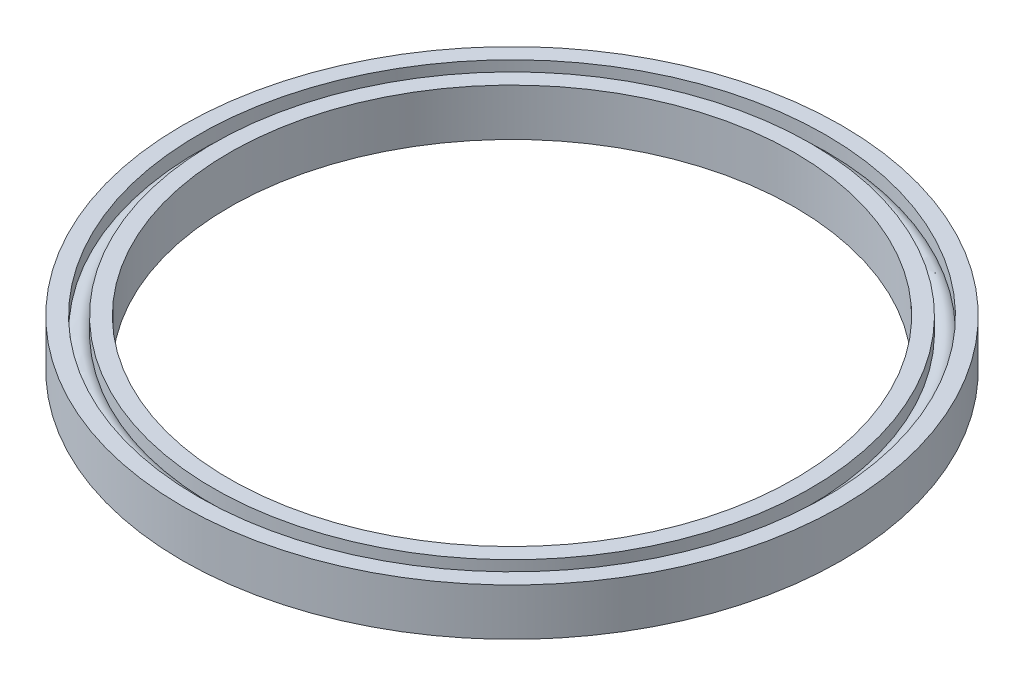
SolidWorks part; units mm, degrees
material "镀铬不锈钢"
ref_plane "前视基准面" through (0, 0, 0) normal (0, 0, 1) x (1, 0, 0)
ref_plane "上视基准面" through (0, 0, 0) normal (0, 1, 0) x (1, 0, 0)
ref_plane "右视基准面" through (0, 0, 0) normal (1, 0, 0) x (0, 0, -1)
other "Configuration Table"
sketch "草图1" plane through (0, 0, 0) normal (0, 0, 1) x (1, 0, 0)
  line L2 (38.1, 6.35) -> (40.275, 6.35)
  line L3 (38.1, 6.35) -> (38.1, 0)
  line L4 (38.1, 0) -> (40.275, 0)
  line L5 (40.275, 6.35) -> (40.275, 4.4079)
  line L6 (42.275, 6.35) -> (44.45, 6.35)
  line L7 (42.275, 6.35) -> (42.275, 4.4079)
  line L8 (42.275, 0) -> (44.45, 0)
  line L9 (44.45, 6.35) -> (44.45, 0)
  line L10 (42.275, 1.9421) -> (42.275, 0)
  line L11 (40.275, 1.9421) -> (40.275, 0)
  line L51 (44.45, 0) -> (57.45, 0)
  line L52 (44.45, 0) -> (44.45, 6.1)
  line L53 (44.45, 6.1) -> (57.45, 6.1)
  line L54 (57.45, 0) -> (57.45, 6.1)
  line L56 (38.1, 0) -> (38.1, 6.1)
  line L57 (38.1, 6.1) -> (25.1, 6.1)
  line L58 (25.1, 0) -> (25.1, 6.1)
  line L63 (40.275, 0) -> (25.1, 0)
  line L71 (44.45, 6.35) -> (57.275, 6.35)
  line L75 (42.275, 6.35) -> (57.275, 6.35)
  line L76 (42.275, 6.35) -> (42.275, 9.35)
  line L77 (42.275, 9.35) -> (57.275, 9.35)
  line L78 (57.275, 6.35) -> (57.275, 9.35)
  line L79 (30.1, 6.35) -> (34.1, 6.35)
  line L80 (30.1, 6.35) -> (30.1, -4) construction
  line L81 (30.1, -4) -> (34.1, -4)
  line L82 (34.1, 6.35) -> (34.1, -4) construction
  line L83 (48.45, 9.35) -> (52.45, 9.35)
  line L84 (48.45, 9.35) -> (48.45, -4) construction
  line L86 (52.45, 9.35) -> (52.45, -4) construction
  line L91 (40.275, 6.35) -> (-43.4824, 6.35)
  line L94 (-43.4824, 6.35) -> (-43.4824, 10.35)
  line L95 (40.275, 0) -> (25.275, 0)
  line L96 (40.275, 0) -> (40.275, -4)
  line L97 (40.275, -4) -> (25.275, -4)
  line L98 (25.275, 0) -> (25.275, -4)
  line L99 (40.275, 6.35) -> (25.275, 6.35)
  line L101 (25.275, 10.35) -> (25.275, 6.35)
  line L104 (40.275, 6.35) -> (40.275, 10.35)
  line L105 (40.275, 10.35) -> (25.275, 10.35)
  line L108 (30.1, 6.35) -> (30.1, 10.35) construction
  line L109 (34.1, 6.35) -> (34.1, 10.35) construction
  line L110 (0, 13.35) -> (0, 20.3048) construction
  line L111 (44.45, 3.175) -> (41.275, 3.175) construction
  line L112 (42.275, 0) -> (142.275, 0)
  line L113 (42.275, 0) -> (42.275, -4)
  line L114 (42.275, -4) -> (142.275, -4)
  line L115 (142.275, 0) -> (142.275, -4)
  line L116 (41.275, 5.7726) -> (41.275, 0.3225) construction
  circle A0 centre (41.275, 3.175) radius 1.5875
  point P51 (0, 13.35)
  dimension "D4" = 3.175
  dimension "D3" = 6.1
  dimension "D5" = 2
  dimension "D6" = 6.1
  dimension "D7" = 6.35
  dimension "D8" = 13
  dimension "D9" = 13
  dimension "D10" = 4
  dimension "D11" = 76.2
  dimension "D12" = 88.9
  dimension "D13" = 15
  dimension "D14" = 4
  dimension "D15" = 15
  dimension "D16" = 3
  dimension "D17" = 4
  dimension "D18" = 4
  dimension "D19" = 100
  dimension "D20" = 5
  dimension "D21" = 5
  dimension "D22" = 4
  dimension "D23" = 15
revolve "旋转1" add sketch "草图1" angle 360 about L110
